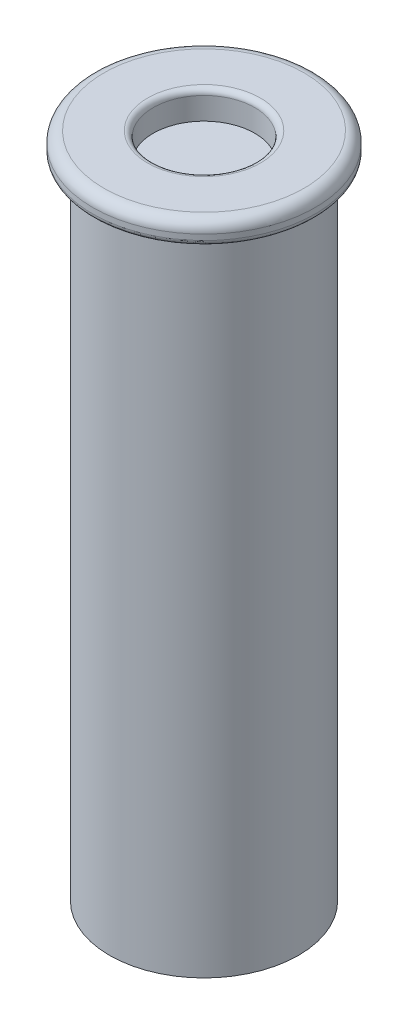
SolidWorks part; units mm, degrees
ref_plane "Front Plane" through (0, 0, 0) normal (0, 0, 1) x (1, 0, 0)
ref_plane "Top Plane" through (0, 0, 0) normal (0, 1, 0) x (1, 0, 0)
ref_plane "Right Plane" through (0, 0, 0) normal (1, 0, 0) x (0, 0, -1)
ref_plane "Plane1"
sketch "Sketch1" plane through (0, 0, 0) normal (0, 0, 1) x (1, 0, 0)
  line L1 (17, 0) -> (17, 106)
  line L2 (17, 106) -> (20, 106)
  line L3 (20, 106) -> (20, 110)
  line L4 (20, 110) -> (0, 110)
  line L5 (0, 110) -> (0, 0)
  line L6 (0, 0) -> (17, 0)
  line L7 (0, 0) -> (0, 110) construction
  dimension "D1" = 110
  dimension "D2" = 20
  dimension "D3" = 4
  dimension "D4" = 3
  dimension "D5" = 106
revolve "Revolution1" add sketch "Sketch1" angle 360 about L7
sketch "Sketch2" plane through (0, 0, 0) normal (0, -1, 0) x (1, 0, 0)
  circle A0 centre (0, 0) radius 17
  circle A1 centre (0, 0) radius 2.4
  circle A2 centre (0, 0) radius 2.4
  dimension "D1" = 34
  dimension "D2" = 4.8
extrude "Extrusion4" add sketch "Sketch2" along normal blind 10
sketch "Sketch3" plane through (0, 110, 0) normal (0, 1, 0) x (-1, 0, 0)
  circle A0 centre (0, 0) radius 9.15
  dimension "D1" = 18.3
extrude "Extrusion5" cut sketch "Sketch3" against normal blind 5
fillet "Fillet2" radius 1 1 edges at (0, 110, 9.15)
fillet "Fillet3" radius 2 1 edges at (0, 110, -20)
fillet "Fillet4" radius 1 1 edges at (0, 106, -20)
fillet "Fillet5" radius 1 1 edges at (0, 106, -17)
sketch "Sketch4" plane through (0, -10, 0) normal (0, -1, 0) x (1, 0, 0)
  circle A1 centre (0, 0) radius 2.75
  dimension "D1" = 5.5
extrude "Cut-Extrude3" cut sketch "Sketch4" against normal blind 12
sketch "Sketch5" plane through (0, -10, 0) normal (0, -1, 0) x (1, 0, 0)
  circle A0 centre (0, 0) radius 3.25
  dimension "D1" = 6.5
extrude "Cut-Extrude4" cut sketch "Sketch5" against normal blind 1
